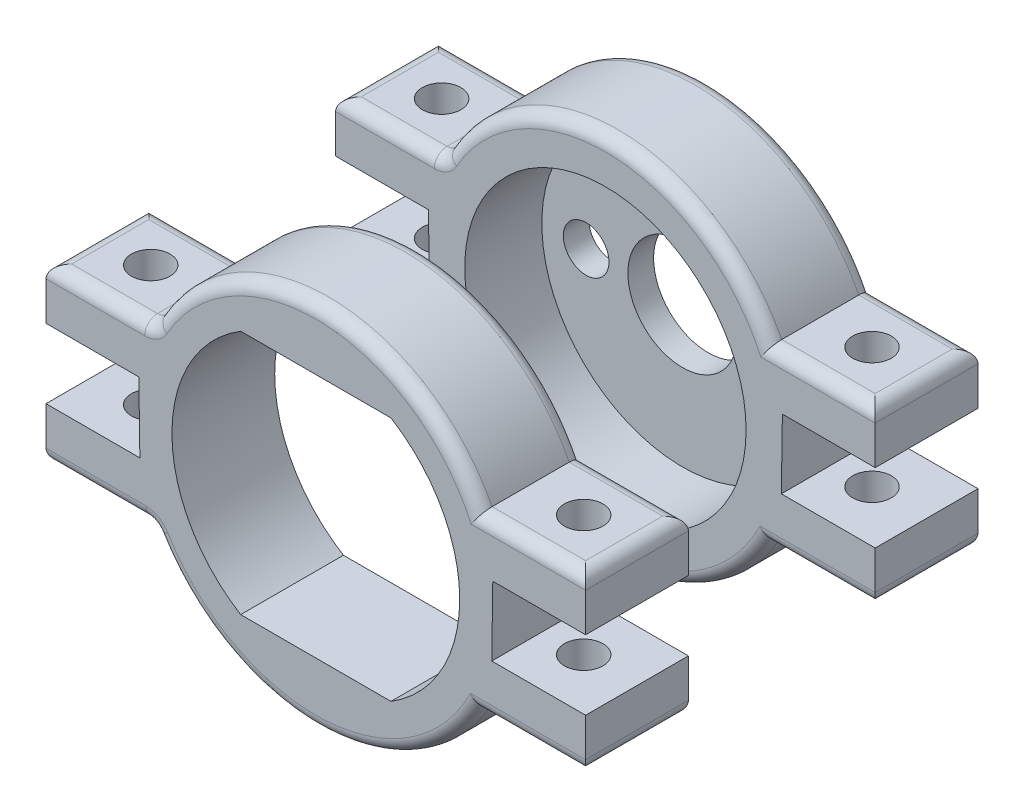
SolidWorks part; units mm, degrees
ref_plane "Alzado" through (0, 0, 0) normal (0, 0, 1) x (1, 0, 0)
ref_plane "Planta" through (0, 0, 0) normal (0, 1, 0) x (1, 0, 0)
ref_plane "Vista lateral" through (0, 0, 0) normal (1, 0, 0) x (0, 0, -1)
sketch "Croquis1" plane through (0, 0, 0) normal (0, 0, 1) x (1, 0, 0)
  line L0 (0, 2.5054) -> (0, -2.9098) construction
  line L1 (-13.774, 2.5054) -> (-23.9049, 2.5054)
  line L2 (-23.9049, 2.5054) -> (-23.9049, 6.5054)
  line L3 (-13.6943, -2.9098) -> (-23.8251, -2.9098)
  line L4 (-23.9049, 6.5054) -> (-12.7249, 6.5054)
  line L5 (-23.8251, -2.9098) -> (-23.8251, -6.9098)
  line L6 (-23.8251, -6.9098) -> (-12.6451, -6.9098)
  line L7 (23.8251, -6.9098) -> (12.6451, -6.9098)
  line L8 (23.9049, 6.5054) -> (12.7249, 6.5054)
  line L9 (13.6943, -2.9098) -> (23.8251, -2.9098)
  line L10 (13.774, 2.5054) -> (23.904, 2.5054)
  line L11 (23.8251, -2.9098) -> (23.8251, -6.9098)
  line L12 (23.904, 2.5054) -> (23.9049, 6.5054)
  arc A0 (12.7249, 6.5054) -> (-12.7249, 6.5054) centre (0, 0) ccw
  arc A1 (-13.774, 2.5054) -> (-13.6943, -2.9098) centre (0, 0) ccw
  arc A2 (-12.6451, -6.9098) -> (12.6451, -6.9098) centre (0, 0) ccw
  arc A3 (13.6943, -2.9098) -> (13.774, 2.5054) centre (0, 0) ccw
  dimension "D1" = 14
  dimension "D2" = 10.1309
  dimension "D3" = 10.1309
  dimension "D4" = 11.18
  dimension "D5" = 11.18
  dimension "D6" = 4
  dimension "D7" = 4
  dimension "D8" = 4
  dimension "D9" = 5.4152
  dimension "D10" = 23.9049
  dimension "D11" = 10.13
extrude "Saliente-Extruir1" add sketch "Croquis1" along normal blind 8
ref_plane "Plano1" through (0, 0, 22.54) normal (0, 0, 1) x (1, 0, 0)
sketch "Croquis2" plane through (0, 0, 8) normal (0, 0, 1) x (1, 0, 0)
  circle A0 centre (0, 0) radius 10.95
  dimension "D1" = 21.9
extrude "Cortar-Extruir1" cut sketch "Croquis2" against normal blind 6
sketch "Croquis3" plane through (0, 0, 2) normal (0, 0, 1) x (1, 0, 0)
  line L0 (0, 10.95) -> (0, -10.95) construction
  line L1 (-10.95, 0) -> (10.95, 0) construction
  circle A0 centre (0, 0) radius 4.25
  circle A1 centre (0, 0) radius 10.95 construction
  circle A4 centre (-7.5, 0) radius 1.775
  circle A5 centre (7.5, 0) radius 1.775
  dimension "D1" = 8.5
  dimension "D2" = 3.55
  dimension "D3" = 3.55
  dimension "D4" = 7.5
  dimension "D5" = 7.5
extrude "Cortar-Extruir2" cut sketch "Croquis3" against normal blind 3.5
sketch "Croquis6" plane through (0, 0, 22.54) normal (0, 0, 1) x (1, 0, 0)
  line L0 (-12.7249, 6.5054) -> (-24, 6.5054)
  line L1 (-24, 6.5054) -> (-24, 2.5054)
  line L2 (-24, 2.5054) -> (-13.774, 2.5054)
  line L3 (12.6451, -6.9098) -> (23.8251, -6.9098) construction
  line L4 (23.8251, -2.9098) -> (13.6943, -2.9098)
  line L5 (23.8251, -6.9098) -> (23.8251, -2.9098)
  line L6 (12.7224, 6.5102) -> (24, 6.5102)
  line L7 (24, 6.5102) -> (24, 2.5102)
  line L8 (24, 2.5102) -> (13.7731, 2.5102)
  line L9 (12.6451, -6.9098) -> (23.8251, -6.9098)
  line L10 (-23.8251, -2.9098) -> (-13.6943, -2.9098)
  line L11 (-23.8251, -6.9098) -> (-23.8251, -2.9098)
  line L12 (-12.6451, -6.9098) -> (-23.8251, -6.9098)
  line L13 (-23.8251, -6.9098) -> (-12.6451, -6.9098) construction
  line L14 (-12.7249, 6.5054) -> (-23.9049, 6.5054) construction
  line L16 (-23.9049, 2.5054) -> (-13.774, 2.5054) construction
  arc A0 (12.7224, 6.5102) -> (-12.7249, 6.5054) centre (0, 0) ccw
  arc A1 (12.7249, 6.5054) -> (-12.7249, 6.5054) centre (0, 0) ccw construction
  arc A2 (-12.6451, -6.9098) -> (12.6451, -6.9098) centre (0, 0) ccw construction
  arc A3 (12.6451, -6.9098) -> (-12.6451, -6.9098) centre (0, 0) cw
  arc A4 (-13.774, 2.5054) -> (-13.6943, -2.9098) centre (0, 0) ccw
  arc A5 (13.6943, -2.9098) -> (13.7731, 2.5102) centre (0, 0) ccw
  circle A6 centre (0, 0) radius 10.95 construction
  dimension "D5" = 0
  dimension "D6" = 5.42
  dimension "D10" = 14
  dimension "D14" = 0
  dimension "D15" = 0
  dimension "D1" = 4
  dimension "D2" = 4
  dimension "D3" = 10.1309
  dimension "D4" = 11.18
  dimension "D7" = 4
  dimension "D8" = 11.18
  dimension "D9" = 4
  dimension "D11" = 4
  dimension "D12" = 0
  dimension "D13" = 24
  dimension "D16" = 24
  dimension "D17" = 0
  dimension "D18" = 0
extrude "Saliente-Extruir3" add sketch "Croquis6" along normal blind 8
sketch "Croquis7" plane through (0, 0, 30.54) normal (0, 0, 1) x (1, 0, 0)
  line L0 (-5.8487, 9.5516) -> (5.8487, 9.5516)
  line L1 (-5.8487, -9.5516) -> (5.8487, -9.5516)
  arc A0 (-5.8487, 9.5516) -> (-5.8487, -9.5516) centre (0, 0) ccw
  arc A1 (5.8487, -9.5516) -> (5.8487, 9.5516) centre (0, 0) ccw
  dimension "D1" = 11.2
  dimension "D4" = 11.2
  dimension "D2" = 11.6974
  dimension "D3" = 11.6974
extrude "Cortar-Extruir8" cut sketch "Croquis7" against normal blind 10
sketch "Croquis8" plane through (0, 6.5054, 0) normal (0, 1, 0) x (1, 0, 0)
  line L6 (23.9049, 0) -> (12.7249, 0) construction
  line L7 (24, -30.54) -> (12.7224, -30.54) construction
  line L8 (0, -4) -> (0, -26.5) construction
  line L9 (-23.9049, -8) -> (-23.9049, 0) construction
  line L10 (-24, -30.54) -> (-24, -22.54) construction
  circle A0 centre (16.85, -26.54) radius 1.5
  circle A1 centre (16.7501, -4) radius 1.5
  circle A2 centre (-16.7501, -4) radius 1.5
  circle A3 centre (-16.85, -26.54) radius 1.5
  dimension "D1" = 3
  dimension "D2" = 3
  dimension "D5" = 4
  dimension "D6" = 4
  dimension "D7" = 7.1548
  dimension "D8" = 7.15
sketch "Croquis11" plane through (0, 6.5054, 0) normal (0, 1, 0) x (1, 0, 0)
  line L0 (23.9049, 0) -> (12.7249, 0) construction
  line L5 (24, -31) -> (21, -31)
  line L10 (-12.7249, 0) -> (-23.9049, 0) construction
  line L11 (-24, -30.54) -> (-21, -30.54)
  line L12 (-24, -30.54) -> (-24, 0)
  line L13 (-24, 0) -> (-21, 0)
  line L14 (-21, -30.54) -> (-21, 0)
  line L15 (24, -31) -> (24, 0)
  line L16 (24, 0) -> (21, 0)
  line L17 (21, -31) -> (21, 0)
  line L18 (24, -30.54) -> (24, -22.54) construction
  dimension "D1" = 3
  dimension "D2" = 3
  dimension "D3" = 0
  dimension "D4" = 31
extrude "Cortar-Extruir9" cut sketch "Croquis11" against normal through all both and the other way through all
extrude "Cortar-Extruir10" cut sketch "Croquis8" against normal through all both and the other way through all
fillet "Redondeo1" radius 1 18 edges at (16.8624, 6.5054, 8) (16.8624, 6.5054, 0) (-16.8624, 6.5054, 0) (-16.8624, 6.5054, 8) (-21, 6.5054, 4) (16.8226, -6.9098, 0) (16.8226, -6.9098, 8) (-16.8226, -6.9098, 8) (-16.8226, -6.9098, 0) (-21, -6.9098, 4) (21, -6.9098, 4) (21, 6.5054, 4) (0, 14.2913, 0) (0, 14.2913, 8) (0, -14.4099, 0) (0, -14.4099, 8) (-12.7249, 6.5054, 4) (-12.6451, -6.9098, 4)
fillet "Redondeo2" radius 1 18 edges at (16.8612, 6.5102, 22.54) (16.8612, 6.5102, 30.54) (-16.8624, 6.5054, 22.54) (-21, 6.5054, 26.54) (-16.8624, 6.5054, 30.54) (16.8226, -6.9098, 22.54) (16.8226, -6.9098, 30.54) (-16.8226, -6.9098, 30.54) (-16.8226, -6.9098, 22.54) (-21, -6.9098, 26.54) (21, 6.5102, 26.54) (21, -6.9098, 26.54) (0, -14.4099, 30.54) (0, -14.4099, 22.54) (-0.0027, 14.2913, 30.54) (-0.0027, 14.2913, 22.54) (-12.6451, -6.9098, 26.54) (-12.7249, 6.5054, 26.54)
sketch "Croquis12" plane through (0, 0, 0) normal (0, 0, -1) x (-1, 0, 0)
  line L0 (-13.774, 2.5054) -> (-13.6943, -2.9098)
  line L1 (13.774, 2.5054) -> (13.6943, -2.9098)
  arc A0 (-13.774, 2.5054) -> (-13.6943, -2.9098) centre (0, 0) ccw
  arc A1 (13.774, 2.5054) -> (13.6943, -2.9098) centre (0, 0) cw
  dimension "D1" = 14
  dimension "D2" = 14
extrude "Cortar-Extruir11" cut sketch "Croquis12" against normal through all
